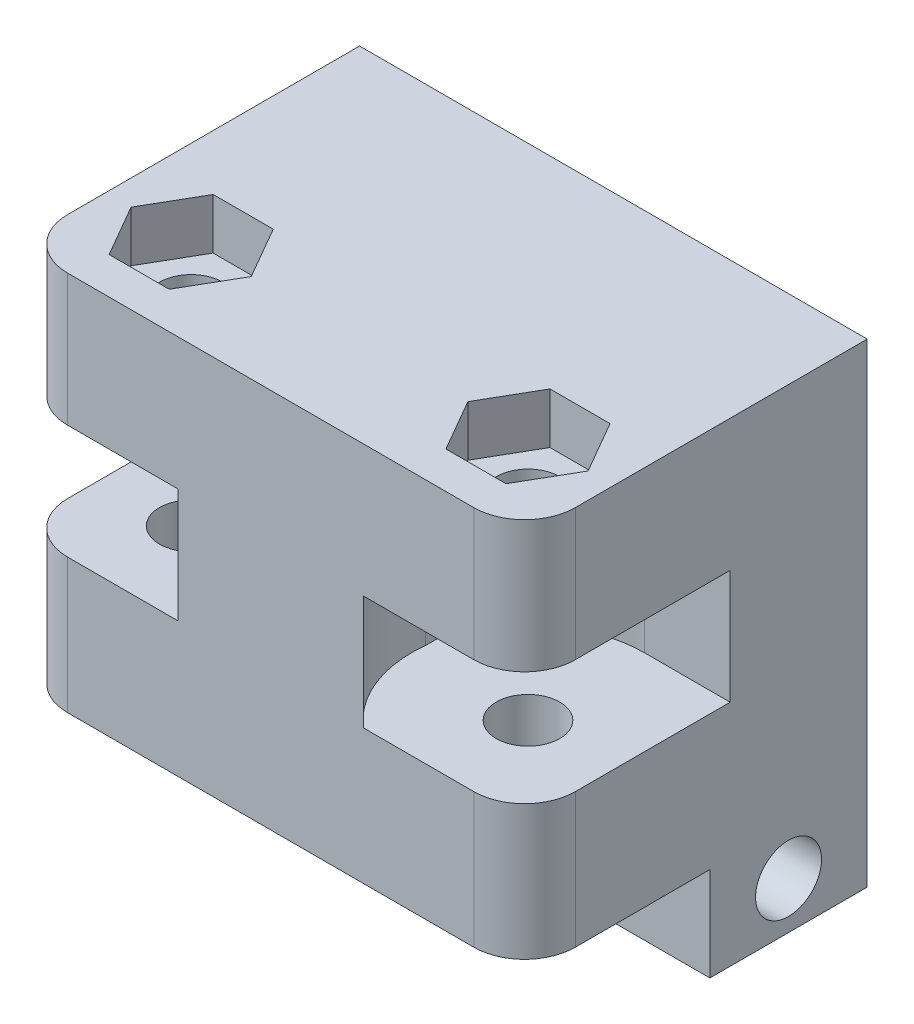
SolidWorks part; units mm, degrees
ref_plane "Front Plane" through (0, 0, 0) normal (0, 0, 1) x (1, 0, 0)
ref_plane "Top Plane" through (0, 0, 0) normal (0, 1, 0) x (1, 0, 0)
ref_plane "Right Plane" through (0, 0, 0) normal (1, 0, 0) x (0, 0, -1)
sketch "Sketch1" plane through (0, 0, 0) normal (0, 1, 0) x (1, 0, 0)
  line L1 (-22.8462, -9.1868) -> (17.1538, -9.1868)
  line L2 (-22.8462, -9.1868) -> (-22.8462, 17.8132)
  line L3 (-22.8462, 17.8132) -> (17.1538, 17.8132)
  line L4 (17.1538, -9.1868) -> (17.1538, 17.8132)
  dimension "D1" = 27
  dimension "D2" = 40
extrude "Boss-Extrude1" add sketch "Sketch1" along normal blind 30
sketch "Sketch2" plane through (0, 0, -17.8132) normal (0, 0, -1) x (-1, 0, 0)
  line L0 (2.8462, 30) -> (2.8462, 0) construction
  line L1 (-8.0864, 4) -> (-0.2064, 4)
  line L2 (-0.2064, 4) -> (-0.2064, 7)
  line L3 (-0.2064, 7) -> (-2.8664, 7)
  line L4 (-2.8664, 7) -> (-2.8664, 8.0087)
  line L5 (-2.8664, 8.0087) -> (-0.2538, 10.6287)
  line L6 (-0.2538, 10.6287) -> (5.9462, 10.6287)
  line L7 (-17.1538, 30) -> (22.8462, 30) construction
  line L8 (-17.1538, 0) -> (22.8462, 0) construction
  line L9 (-8.0864, 4) -> (-8.0864, 26)
  line L10 (-8.0864, 26) -> (-0.2064, 26)
  line L11 (-0.2064, 26) -> (-0.2064, 23)
  line L12 (-0.2064, 23) -> (-2.8664, 23)
  line L13 (-2.8664, 23) -> (-2.8664, 21.9913)
  line L14 (-2.8664, 21.9913) -> (-0.2464, 19.3787)
  line L15 (-0.2464, 19.3787) -> (5.9536, 19.3787)
  line L16 (-17.1538, 15) -> (22.8462, 15) construction
  line L17 (-17.1538, 30) -> (-17.1538, 0) construction
  line L18 (22.8462, 30) -> (22.8462, 0) construction
  line L19 (5.9387, 19.3787) -> (-0.2613, 19.3787)
  line L20 (8.5587, 21.9913) -> (5.9387, 19.3787)
  line L21 (8.5587, 23) -> (8.5587, 21.9913)
  line L22 (5.8987, 23) -> (8.5587, 23)
  line L23 (5.8987, 26) -> (5.8987, 23)
  line L24 (13.7787, 26) -> (5.8987, 26)
  line L25 (13.7787, 4) -> (13.7787, 26)
  line L26 (8.5587, 8.0087) -> (5.9462, 10.6287)
  line L27 (8.5587, 7) -> (8.5587, 8.0087)
  line L28 (5.8987, 7) -> (8.5587, 7)
  line L29 (5.8987, 4) -> (5.8987, 7)
  line L30 (13.7787, 4) -> (5.8987, 4)
  point P26 (-8.0864, 15)
  point P27 (2.8462, 15)
  point P37 (2.8462, 10.6287)
  dimension "D1" = 6.2
  dimension "D2" = 2.62
  dimension "D3" = 3.7
  dimension "D4" = 8.75
  dimension "D5" = 7.88
  dimension "D6" = 22
  dimension "D7" = 5.22
  dimension "D8" = 3
  dimension "D9" = 90
extrude "Cut-Extrude1" cut sketch "Sketch2" against normal blind 10
sketch "Sketch3" plane through (0, 0, 0) normal (0, -1, 0) x (1, 0, 0)
  line L0 (-22.8462, 9.1868) -> (17.1538, 9.1868) construction
  line L1 (17.1538, 9.1868) -> (17.1538, -17.8132) construction
  line L2 (-2.8462, 9.1868) -> (-2.8462, -17.8132) construction
  line L3 (17.1538, -17.8132) -> (-22.8462, -17.8132) construction
  circle A0 centre (10.4238, 2.1868) radius 2.5
  circle A2 centre (-16.1162, 2.1868) radius 2.5
  dimension "D1" = 5
  dimension "D3" = 7
  dimension "D4" = 6.73
extrude "Cut-Extrude2" cut sketch "Sketch3" against normal blind 30
sketch "Sketch8" plane through (0, 0, 0) normal (0, -1, 0) x (1, 0, 0)
  line L0 (4.4539, 9.1868) -> (17.1538, 9.1868)
  line L1 (-22.8462, 9.1868) -> (17.1538, 9.1868) construction
  line L2 (17.1538, 9.1868) -> (17.1538, -7.0132)
  line L3 (17.1538, 9.1868) -> (17.1538, -17.8132) construction
  line L4 (17.1538, -7.0132) -> (10.4238, -7.0132)
  line L6 (-2.8462, -17.8132) -> (-2.8462, 9.1868) construction
  line L7 (17.1538, -17.8132) -> (-22.8462, -17.8132) construction
  line L8 (-22.8462, -7.0132) -> (-16.1162, -7.0132)
  line L9 (-22.8462, 9.1868) -> (-22.8462, -7.0132)
  line L10 (-10.1462, 9.1868) -> (-22.8462, 9.1868)
  arc A0 (10.4238, -7.0132) -> (4.4539, 9.1868) centre (10.4238, 2.1868) cw
  arc A1 (-16.1162, -7.0132) -> (-10.1462, 9.1868) centre (-16.1162, 2.1868) ccw
  dimension "D1" = 9.2
  dimension "D2" = 6.73
extrude "Cut-Extrude5" cut sketch "Sketch8" against normal blind 9 from offset 10.62 offset against normal yes
sketch "Sketch10" plane through (8.0864, 0, 0) normal (-1, 0, 0) x (0, 0, 1)
  line L0 (-17.8132, 30) -> (-17.8132, 0) construction
  line L1 (-17.8132, 18.82) -> (2.1868, 18.82)
  line L2 (-17.8132, 18.82) -> (-17.8132, 10.62)
  line L3 (-17.8132, 10.62) -> (2.1868, 10.62)
  line L4 (2.1868, 18.82) -> (2.1868, 10.62)
  line L5 (-17.8132, 30) -> (9.1868, 30) construction
  dimension "D1" = 20
  dimension "D2" = 11.18
  dimension "D3" = 8.2
extrude "Cut-Extrude7" cut sketch "Sketch10" along normal blind 6.8
sketch "Sketch12" plane through (-13.7787, 0, 0) normal (1, 0, 0) x (0, 0, -1)
  line L1 (17.8132, 18.82) -> (-2.1868, 18.82)
  line L2 (17.8132, 18.82) -> (17.8132, 10.62)
  line L3 (17.8132, 10.62) -> (-2.1868, 10.62)
  line L4 (-2.1868, 18.82) -> (-2.1868, 10.62)
  line L5 (-9.1868, 30) -> (17.8132, 30) construction
  dimension "D1" = 20
  dimension "D2" = 8.2
  dimension "D3" = 11.18
extrude "Cut-Extrude10" cut sketch "Sketch12" along normal blind 6.8
fillet "Fillet1" radius 4 4 edges at (17.1538, 5.31, 9.1868) (17.1538, 24.81, 9.1868) (-22.8462, 5.31, 9.1868) (-22.8462, 24.81, 9.1868)
sketch "Sketch13" plane through (17.1538, 0, 0) normal (1, 0, 0) x (0, 0, -1)
  line L0 (-5.1868, 0) -> (17.8132, 0) construction
  line L1 (17.8132, 30) -> (17.8132, 0) construction
  line L3 (17.8132, 0) -> (5.4132, 0)
  line L4 (17.8132, 0) -> (17.8132, -7.4)
  line L5 (17.8132, -7.4) -> (5.4132, -7.4)
  line L6 (5.4132, 0) -> (5.4132, -7.4)
  circle A0 centre (11.6132, -3.7) radius 2.6
  dimension "D1" = 6.2
  dimension "D2" = 3.7
  dimension "D3" = 5.2
  dimension "D4" = 12.4
  dimension "D5" = 7.4
extrude "Boss-Extrude2" add sketch "Sketch13" against normal up to surface (40 mm away) up to face at (-22.8462, 15.06, -3.6132)
sketch "Sketch14" plane through (0, 0, -5.4132) normal (0, 0, 1) x (1, 0, 0)
  line L0 (-22.8462, -7.4) -> (17.1538, -7.4) construction
  line L1 (-12.8462, -7.4) -> (7.1538, -7.4)
  line L2 (-12.8462, -7.4) -> (-12.8462, 0)
  line L3 (-12.8462, 0) -> (7.1538, 0)
  line L4 (7.1538, -7.4) -> (7.1538, 0)
  line L5 (-18.8462, 0) -> (13.1538, 0) construction
  line L7 (17.1538, 0) -> (17.1538, -7.4) construction
  dimension "D1" = 20
  dimension "D2" = 10
extrude "Cut-Extrude11" cut sketch "Sketch14" against normal up to next
sketch "Sketch15" plane through (0, 30, 0) normal (0, 1, 0) x (1, 0, 0)
  line L1 (12.791, -6.2868) -> (15.1581, -2.1868)
  line L2 (15.1581, -2.1868) -> (12.791, 1.9132)
  line L3 (12.791, 1.9132) -> (8.0567, 1.9132)
  line L4 (8.0567, 1.9132) -> (5.6896, -2.1868)
  line L5 (5.6896, -2.1868) -> (8.0567, -6.2868)
  line L6 (8.0567, -6.2868) -> (12.791, -6.2868)
  line L7 (-13.749, -6.2868) -> (-11.3819, -2.1868)
  line L8 (-11.3819, -2.1868) -> (-13.749, 1.9132)
  line L9 (-13.749, 1.9132) -> (-18.4833, 1.9132)
  line L10 (-18.4833, 1.9132) -> (-20.8504, -2.1868)
  line L11 (-20.8504, -2.1868) -> (-18.4833, -6.2868)
  line L12 (-18.4833, -6.2868) -> (-13.749, -6.2868)
  circle A0 centre (-16.1162, -2.1868) radius 2.5 construction
  circle A1 centre (10.4238, -2.1868) radius 2.5 construction
  circle A2 centre (-16.1162, -2.1868) radius 2.5
  circle A3 centre (10.4238, -2.1868) radius 2.5
  circle A4 centre (10.4238, -2.1868) radius 4.1 construction
  circle A5 centre (-16.1162, -2.1868) radius 4.1 construction
  dimension "D2" = 8.2
  dimension "D1" = 8.2
extrude "Cut-Extrude12" cut sketch "Sketch15" against normal blind 4
sketch "Sketch16" plane through (0, 0, 0) normal (0, -1, 0) x (1, 0, 0)
  line L1 (-13.749, -1.9132) -> (-11.3819, 2.1868)
  line L2 (-11.3819, 2.1868) -> (-13.749, 6.2868)
  line L3 (-13.749, 6.2868) -> (-18.4833, 6.2868)
  line L4 (-18.4833, 6.2868) -> (-20.8504, 2.1868)
  line L5 (-20.8504, 2.1868) -> (-18.4833, -1.9132)
  line L6 (-18.4833, -1.9132) -> (-13.749, -1.9132)
  line L7 (12.791, -1.9132) -> (15.1581, 2.1868)
  line L8 (15.1581, 2.1868) -> (12.791, 6.2868)
  line L9 (12.791, 6.2868) -> (8.0567, 6.2868)
  line L10 (8.0567, 6.2868) -> (5.6896, 2.1868)
  line L11 (5.6896, 2.1868) -> (8.0567, -1.9132)
  line L12 (8.0567, -1.9132) -> (12.791, -1.9132)
  circle A0 centre (10.4238, 2.1868) radius 2.5 construction
  circle A1 centre (-16.1162, 2.1868) radius 2.5 construction
  circle A2 centre (10.4238, 2.1868) radius 2.5
  circle A3 centre (-16.1162, 2.1868) radius 2.5
  circle A4 centre (-16.1162, 2.1868) radius 4.1 construction
  circle A5 centre (10.4238, 2.1868) radius 4.1 construction
  dimension "D1" = 8.2
  dimension "D2" = 8.2
extrude "Cut-Extrude13" cut sketch "Sketch16" against normal blind 4
